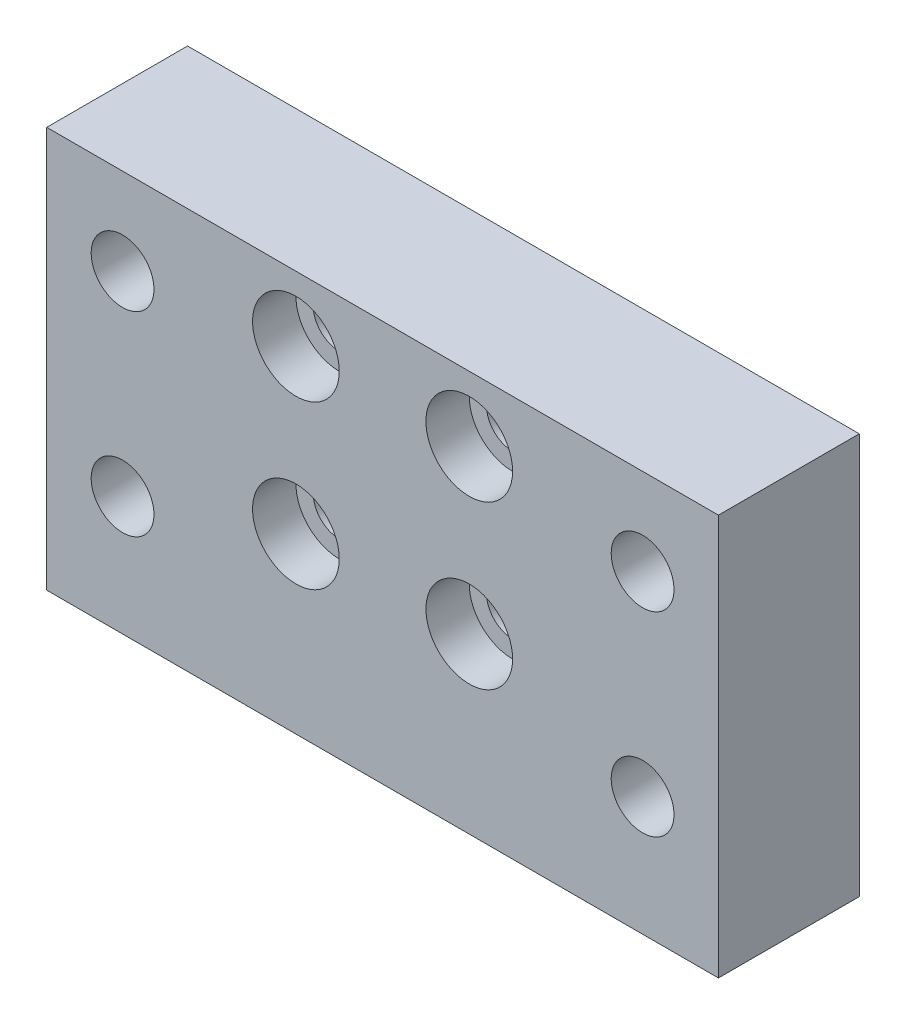
SolidWorks part; units mm, degrees
material "SKD11淬火HRC56-60"
ref_plane "前基準面" through (0, 0, 0) normal (0, 0, 1) x (1, 0, 0)
ref_plane "上基準面" through (0, 0, 0) normal (0, 1, 0) x (1, 0, 0)
ref_plane "右基準面" through (0, 0, 0) normal (1, 0, 0) x (0, 0, -1)
sketch "草图1" plane through (0, 0, 0) normal (0, 0, 1) x (1, 0, 0)
  line L1 (0, 0) -> (62, 0)
  line L2 (0, 0) -> (0, 37)
  line L3 (0, 37) -> (62, 37)
  line L4 (62, 0) -> (62, 37)
  dimension "D1" = 62
  dimension "D2" = 37
extrude "凸台-拉伸1" add sketch "草图1" along normal blind 13
hole_wizard "M5 六角凹头螺钉的柱形沉头孔1" positions "草图3" profile "草图2" counterbore size "M5" standard "ISO" end condition through all
sketch "草图3" plane through (0, 0, 0) normal (0, 0, -1) x (-1, 0, 0)
  line L0 (-31, 37) -> (-31, 0) construction
  line L1 (-62, 37) -> (0, 37) construction
  line L2 (0, 0) -> (-62, 0) construction
  point P0 (-7, 11)
  point P1 (-7, 29)
  point P3 (-55, 11)
  point P5 (-55, 29)
  dimension "D1" = 8
  dimension "D2" = 48
  dimension "D3" = 18
sketch "草图2" plane through (7, 11, 0) normal (1, 0, 0) x (0, 1, 0)
  line L0 (0, 0) -> (0, 13)
  line L1 (0, 13) -> (2.9, 13)
  line L3 (2.9, 13) -> (2.9, 5)
  line L4 (2.9, 5) -> (5, 5)
  line L5 (5, 5) -> (5, 0)
  line L7 (5, 0) -> (0, 0)
  line L11 (0, -6.35) -> (0, 107.95) construction
  dimension "通孔孔直径" = 5.8
  dimension "通孔孔深度" = 13
  dimension "柱形沉头孔直径" = 10
  dimension "柱形沉头孔深度" = 5
hole_wizard "M4 六角凹头螺钉的柱形沉头孔3" positions "草图7" profile "草图6" counterbore size "M4" standard "ISO" end condition through all
sketch "草图7" plane through (0, 0, 13) normal (0, 0, 1) x (1, 0, 0)
  line L0 (31, 37) -> (31, 11.3677) construction
  line L1 (62, 37) -> (0, 37) construction
  point P0 (39, 16)
  point P3 (23, 16)
  point P5 (23, 31)
  point P7 (39, 31)
  dimension "D1" = 16
  dimension "D2" = 6
  dimension "D3" = 15
sketch "草图6" plane through (39, 16, 13) normal (1, 0, 0) x (0, -1, 0)
  line L0 (0, 0) -> (0, 13)
  line L1 (0, 13) -> (2.4, 13)
  line L3 (2.4, 13) -> (2.4, 4)
  line L4 (2.4, 4) -> (4, 4)
  line L5 (4, 4) -> (4, 0)
  line L7 (4, 0) -> (0, 0)
  line L11 (0, -6.35) -> (0, 107.95) construction
  dimension "通孔孔直径" = 4.8
  dimension "通孔孔深度" = 13
  dimension "柱形沉头孔直径" = 8
  dimension "柱形沉头孔深度" = 4
